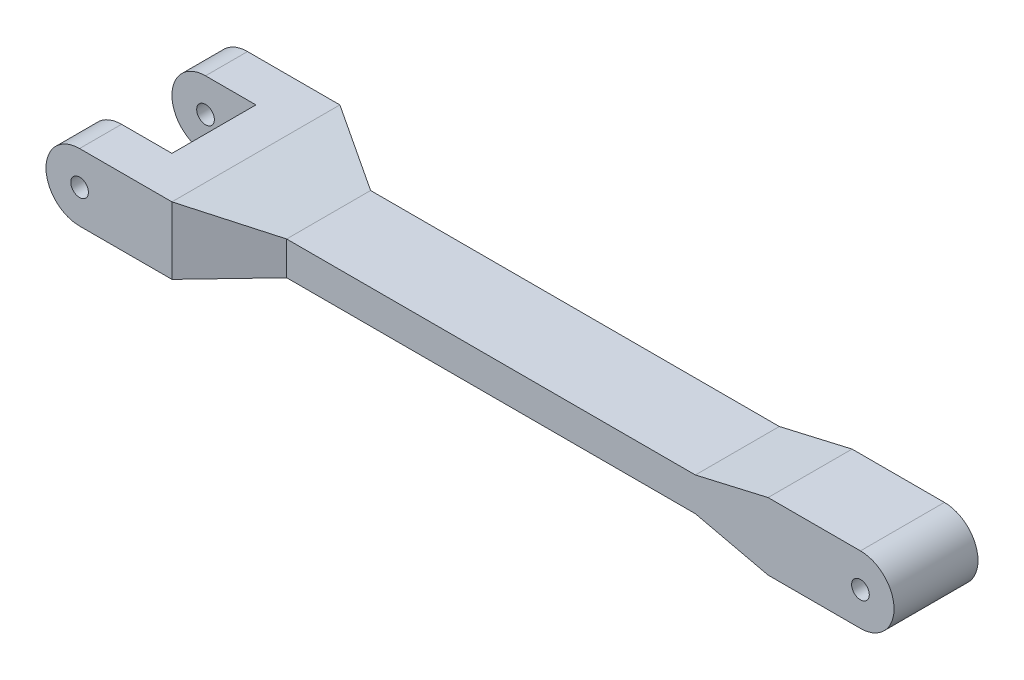
SolidWorks part; units mm, degrees
other "Markup1"
sketch "Sketch12" plane through (139.0831, 6.1121, 25.4) normal (0.0409, 0.0273, 0.9988) x (0.9944, -0.0988, -0.038)
material "6061 Alloy"
ref_plane "Front Plane" through (0, 0, 0) normal (0, 0, 1) x (1, 0, 0)
ref_plane "Top Plane" through (0, 0, 0) normal (0, 1, 0) x (1, 0, 0)
ref_plane "Right Plane" through (0, 0, 0) normal (1, 0, 0) x (0, 0, -1)
sketch "Sketch2" plane through (0, 0, 0) normal (0, 0, 1) x (1, 0, 0)
  line L1 (-10.7769, 6.1121) -> (100.9831, 6.1121)
  line L3 (-10.7769, -4.0479) -> (100.9831, -4.0479)
  arc A0 (-10.7769, 6.1121) -> (-10.7769, -4.0479) centre (-10.7769, 1.0321) ccw
  arc A1 (100.9831, -4.0479) -> (100.9831, 6.1121) centre (100.9831, 1.0321) ccw
  circle A2 centre (-10.7769, 1.0321) radius 1.3375
  circle A3 centre (100.9831, 1.0321) radius 1.3375
  dimension "D3" = 2.675
  dimension "D1" = 10.16
  dimension "D2" = 111.76
  dimension "D6" = 0
extrude "Boss-Extrude2" add sketch "Sketch2" along normal blind 25.4 contours L1 A1 L3 A0
sketch "Sketch4" plane through (0, 6.1121, 0) normal (0, 1, 0) x (1, 0, 0)
  line L0 (-15.8569, 0) -> (-15.8569, -25.4) construction
  line L1 (-3.1569, -6.35) -> (-15.8569, -6.35)
  line L2 (-3.1569, -6.35) -> (-3.1569, -19.05)
  line L3 (-3.1569, -19.05) -> (-15.8569, -19.05)
  line L4 (-15.8569, -6.35) -> (-15.8569, -19.05)
  line L5 (-10.7769, 0) -> (100.9831, 0) construction
  line L6 (-10.7769, -25.4) -> (100.9831, -25.4) construction
  dimension "D1" = 6.35
  dimension "D2" = 6.35
  dimension "D3" = 12.7
extrude "Cut-Extrude2" cut sketch "Sketch4" against normal blind 12.7
sketch "Sketch5" plane through (0, 6.1121, 0) normal (0, 1, 0) x (1, 0, 0)
  line L0 (3.1931, 0) -> (87.0131, 0)
  line L1 (109.0346, -19.05) -> (106.0631, -19.05)
  line L2 (100.9831, -25.4) -> (100.9831, 0) construction
  line L3 (87.0131, -25.4) -> (3.1931, -25.4)
  line L4 (100.9831, -25.4) -> (-10.7769, -25.4) construction
  line L5 (100.9831, 0) -> (-10.7769, 0) construction
  line L6 (-3.1569, -6.35) -> (100.9831, -6.35) construction
  line L7 (-3.1569, -19.05) -> (100.9831, -19.05) construction
  line L8 (3.1931, 0) -> (3.1931, -25.4) construction
  line L9 (87.0131, 0) -> (87.0131, -25.4) construction
  line L10 (-15.8569, 0) -> (-15.8569, -6.35) construction
  line L11 (106.0631, -19.05) -> (106.0631, -25.4)
  line L12 (106.0631, -25.4) -> (87.0131, -25.4)
  line L13 (106.0631, -25.4) -> (106.0631, 0) construction
  line L14 (3.1931, 0) -> (14.1917, -6.35)
  line L15 (14.1917, -6.35) -> (109.0346, -6.35)
  line L17 (3.1931, -25.4) -> (14.1917, -19.05)
  line L18 (14.1917, -19.05) -> (109.0346, -19.05)
  line L20 (109.0346, -6.35) -> (106.0631, -6.35)
  line L21 (106.0631, -6.35) -> (106.0631, 0)
  line L22 (106.0631, 0) -> (87.0131, 0)
  line M10 (-10.7769, -25.4) -> (100.9831, -25.4)
  line M11 (100.9831, -25.4) -> (100.9831, 0)
  line M12 (100.9831, 0) -> (-10.7769, 0)
  dimension "D1" = 19.05
  dimension "D2" = 19.05
  dimension "D3" = 60
  dimension "D4" = 60
extrude "Cut-Extrude3" cut sketch "Sketch5" against normal through all both and the other way through all contours L14 L15 M11 M12 | L18 L17 M10 M11 | L18 L12 L11 M11 | L21 L22 L15 M11
sketch "Sketch8" plane through (0, -4.0479, 0) normal (0, -1, 0) x (1, 0, 0)
  line L0 (100.9831, 19.05) -> (100.9831, 6.35) construction
  line L1 (-3.1569, 19.05) -> (100.9831, 19.05)
  line L2 (-3.1569, 19.05) -> (-3.1569, 6.35)
  line L3 (-3.1569, 6.35) -> (100.9831, 6.35)
  line L4 (100.9831, 19.05) -> (100.9831, 6.35)
extrude "Boss-Extrude4" [suppressed] add sketch "Sketch8" along normal blind 10.16
sketch "Sketch9" [suppressed] plane through (0, 0, 6.35) normal (0, 0, -1) x (-1, 0, 0)
  line L0 (3.1569, -4.0479) -> (3.1569, -14.2079)
  line L2 (3.1569, -14.2079) -> (-134.0031, -14.2079) construction
  line L3 (-14.1917, -14.2079) -> (3.1569, -4.0479)
  line L4 (-14.1917, -14.2079) -> (3.1569, -14.2079)
  line L7 (-111.5746, -14.2079) -> (-128.9228, -14.2079)
  line L9 (-109.0346, -4.0479) -> (-134.0031, -4.0479) construction
  line L11 (-111.5746, -14.2079) -> (-128.9228, -4.0479)
  line L13 (-128.9228, -4.0479) -> (-134.0031, -4.0479)
  line L14 (-134.0031, -4.0479) -> (-134.0031, -14.2079)
  line L15 (-134.0031, -14.2079) -> (-128.9228, -14.2079)
  dimension "D1" = 17.3485
  dimension "D2" = 17.3482
  dimension "D3" = 20.1044
  dimension "D4" = 20.1046
extrude "Cut-Extrude5" [suppressed] cut sketch "Sketch9" against normal through all both and the other way through all
sketch "Sketch10" [suppressed] plane through (0, -14.2079, 0) normal (0, -1, 0) x (1, 0, 0)
  line L14 (14.1917, 6.35) -> (139.0831, 6.35)
  line L15 (14.1917, 6.35) -> (14.1917, 0)
  line L16 (14.1917, 0) -> (139.0831, 0)
  line L17 (139.0831, 6.35) -> (139.0831, 0)
  line L18 (14.1917, 19.05) -> (139.0831, 19.05)
  line L19 (14.1917, 19.05) -> (14.1917, 25.4)
  line L20 (14.1917, 25.4) -> (139.0831, 25.4)
  line L21 (139.0831, 19.05) -> (139.0831, 25.4)
extrude "Cut-Extrude6" [suppressed] cut sketch "Sketch10" against normal through all both and the other way through all
sketch "Sketch13" plane through (0, 0, 25.4) normal (0, 0, 1) x (1, 0, 0)
  line L0 (-15.8569, 1.0321) -> (106.0631, 1.0321) construction
  line L1 (14.1917, -4.0479) -> (14.1917, 6.1121) construction
  line L2 (14.1917, 3.5721) -> (76.0146, 3.5721)
  line L3 (14.1917, 3.5721) -> (14.1917, -1.5079)
  line L4 (14.1917, -1.5079) -> (76.0146, -1.5079)
  line L5 (76.0146, 3.5721) -> (76.0146, -1.5079)
  line L6 (100.9831, 6.1121) -> (100.9831, -4.0479) construction
  line L7 (87.0131, 6.1121) -> (76.0146, 3.5721)
  line L8 (100.9831, 6.1121) -> (87.0131, 6.1121)
  line L9 (3.1931, 6.1121) -> (14.1917, 3.5721)
  line L10 (3.1931, -4.0479) -> (14.1917, -1.5079)
  line L11 (100.9831, 6.1121) -> (100.9831, -4.0479)
  line L12 (100.9831, -4.0479) -> (87.0131, -4.0479)
  line L13 (87.0131, 6.1121) -> (87.0131, -4.0479)
  line L14 (87.0131, -4.0479) -> (76.0146, -1.5079)
  line L15 (3.1931, 6.1121) -> (-10.7769, 6.1121)
  line L16 (87.0131, 6.1121) -> (3.1931, 6.1121)
  line L17 (87.0131, -4.0479) -> (3.1931, -4.0479)
  arc A0 (-10.7769, 6.1121) -> (-10.7769, -4.0479) centre (-10.7769, 1.0321) ccw construction
  arc A1 (100.9831, -4.0479) -> (100.9831, 6.1121) centre (100.9831, 1.0321) ccw construction
  point P14 (14.1917, 1.0321)
  dimension "D1" = 5.08
extrude "Cut-Extrude7" cut sketch "Sketch13" against normal through all contours L7 L16 L9 L2 | L17 L14 L4 L10
